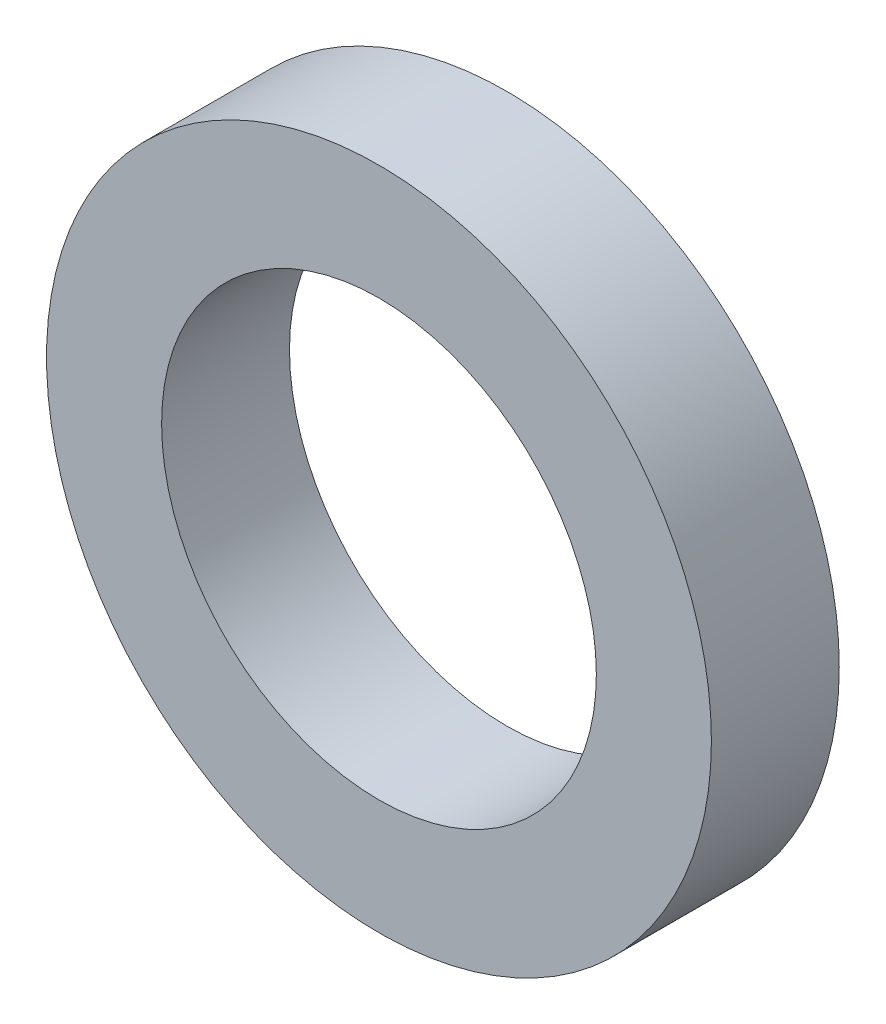
SolidWorks part; units mm, degrees
ref_plane "Ebene vorne" through (0, 0, 0) normal (0, 0, 1) x (1, 0, 0)
ref_plane "Ebene oben" through (0, 0, 0) normal (0, 1, 0) x (1, 0, 0)
ref_plane "Ebene rechts" through (0, 0, 0) normal (1, 0, 0) x (0, 0, -1)
sketch "Skizze1" plane through (0, 0, 0) normal (0, 0, 1) x (1, 0, 0)
  circle A0 centre (0, 0) radius 13
  circle A1 centre (0, 0) radius 8.5
  dimension "D1" = 26
  dimension "D2" = 17
extrude "Aufsatz-Linear austragen1" add sketch "Skizze1" along normal blind 5
